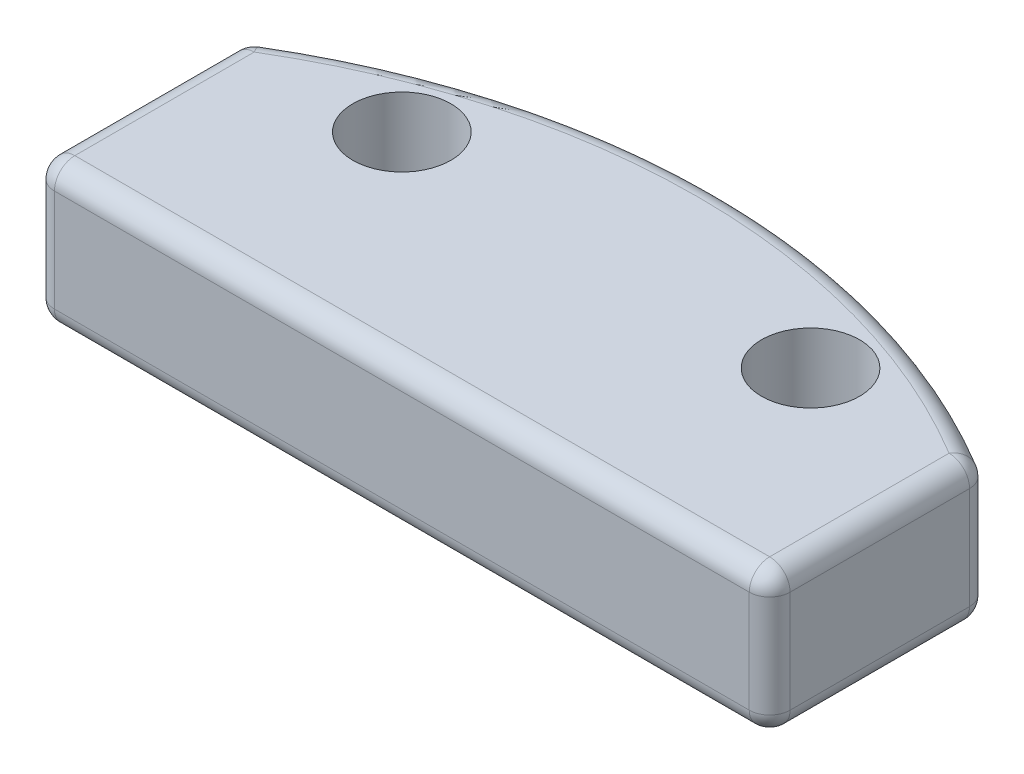
SolidWorks part; units mm, degrees
ref_plane "Front Plane" through (0, 0, 0) normal (0, 0, 1) x (1, 0, 0)
ref_plane "Top Plane" through (0, 0, 0) normal (0, 1, 0) x (1, 0, 0)
ref_plane "Right Plane" through (0, 0, 0) normal (1, 0, 0) x (0, 0, -1)
sketch "Sketch1" plane through (0, 0, 0) normal (0, 1, 0) x (1, 0, 0)
  line L0 (9, -5.17) -> (9, 2.5778) construction
  line L2 (0, 0) -> (0, -5.17)
  line L3 (0, -5.17) -> (18, -5.17)
  line L4 (18, 0) -> (18, -5.17)
  arc A0 (0, 0) -> (18, 0) centre (9, -14.4222) cw
  circle A1 centre (4, -0.17) radius 1.2
  circle A2 centre (14, -0.17) radius 1.2
  dimension "D2" = 17
  dimension "D4" = 10
  dimension "D5" = 2.4
  dimension "D6" = 2.4
  dimension "D1" = 18
  dimension "D3" = 5.17
  dimension "D7" = 5
extrude "Boss-Extrude1" add sketch "Sketch1" along normal blind 3.5
fillet "Fillet1" radius 0.5 12 edges at (9, 3.5, -2.5778) (9, 0, -2.5778) (18, 3.5, 2.585) (18, 1.75, 0) (18, 0, 2.585) (9, 3.5, 5.17) (18, 1.75, 5.17) (9, 0, 5.17) (0, 1.75, 0) (0, 3.5, 2.585) (0, 1.75, 5.17) (0, 0, 2.585)
